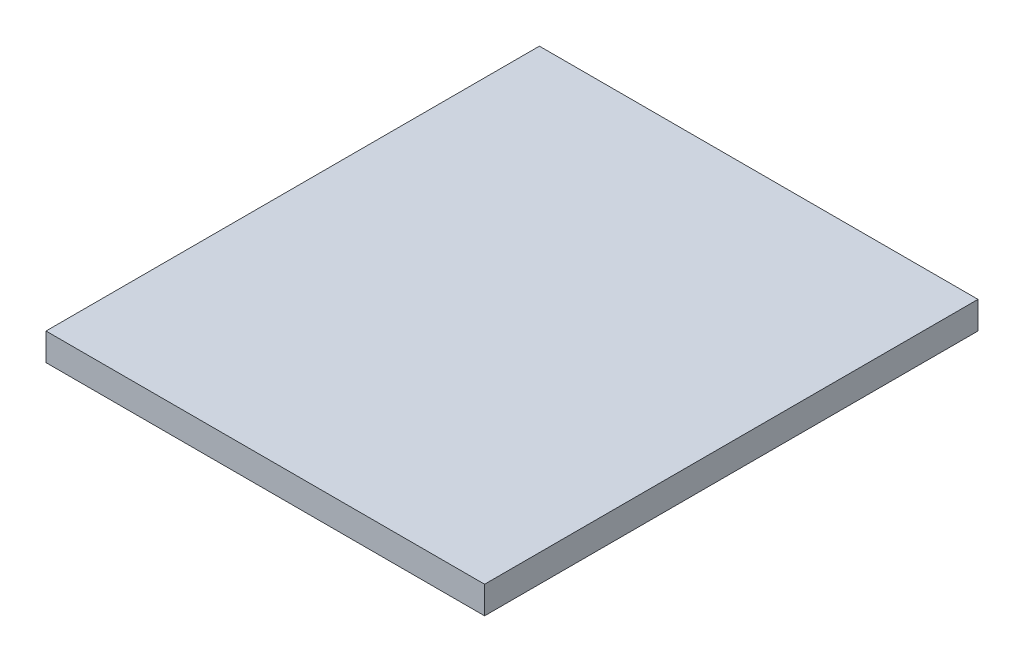
SolidWorks part; units mm, degrees
ref_plane "Front Plane" through (0, 0, 0) normal (0, 0, 1) x (1, 0, 0)
ref_plane "Top Plane" through (0, 0, 0) normal (0, 1, 0) x (1, 0, 0)
ref_plane "Right Plane" through (0, 0, 0) normal (1, 0, 0) x (0, 0, -1)
sketch "Sketch1" plane through (0, 0, 0) normal (0, 1, 0) x (1, 0, 0)
  line L1 (0, 0) -> (50.8, 0)
  line L2 (0, 0) -> (0, 57.15)
  line L3 (0, 57.15) -> (50.8, 57.15)
  line L4 (50.8, 0) -> (50.8, 57.15)
  dimension "D1" = 57.15
  dimension "D2" = 50.8
extrude "Boss-Extrude1" add sketch "Sketch1" along normal blind 3.175
